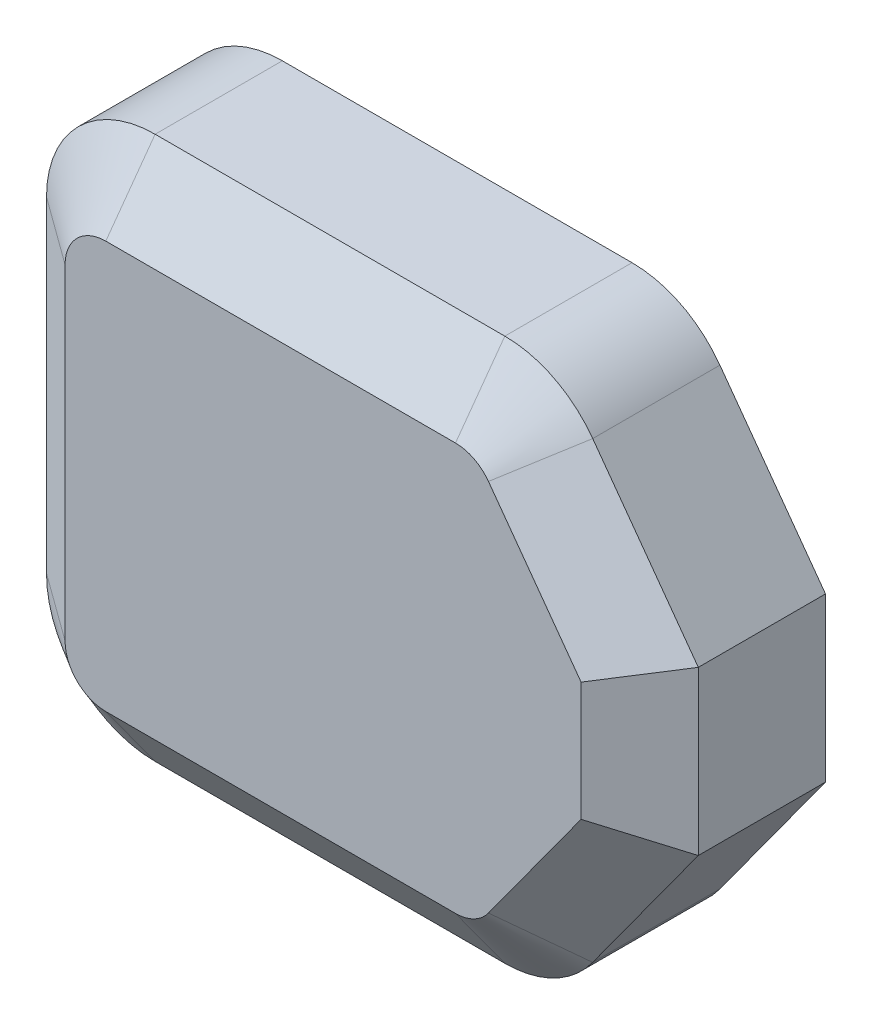
SolidWorks part; units mm, degrees
ref_plane "Plan de face" through (0, 0, 0) normal (0, 0, 1) x (1, 0, 0)
ref_plane "Plan de dessus" through (0, 0, 0) normal (0, 1, 0) x (1, 0, 0)
ref_plane "Plan de droite" through (0, 0, 0) normal (1, 0, 0) x (0, 0, -1)
sketch "Esquisse1" plane through (0, 0, 0) normal (0, 0, 1) x (1, 0, 0)
  line L1 (0, 0) -> (48, 0)
  line L2 (0, 0) -> (0, 40)
  line L3 (0, 40) -> (48, 40)
  line L4 (48, 0) -> (48, 40)
  dimension "D1" = 40
  dimension "D2" = 48
extrude "Boss.-Extru.1" add sketch "Esquisse1" along normal blind 13
fillet "Congé1" radius 8 2 edges at (0, 0, 6.5) (0, 40, 6.5)
chamfer "Chanfrein1" distance 14 angle 36 2 edges at (48, 0, 6.5) (48, 40, 6.5)
fillet "Congé2" radius 8 2 edges at (37.8284, 40, 6.5) (37.8284, 0, 6.5)
chamfer "Chanfrein2" distance 5 angle 36 10 edges at (48, 20, 13) (44.1122, 8.6489, 13) (37.3841, 0.8719, 13) (20.8761, 0, 13) (2.3431, 2.3431, 13) (0, 20, 13) (2.3431, 37.6569, 13) (20.8761, 40, 13) (37.3841, 39.1281, 13) (44.1122, 31.3511, 13)
